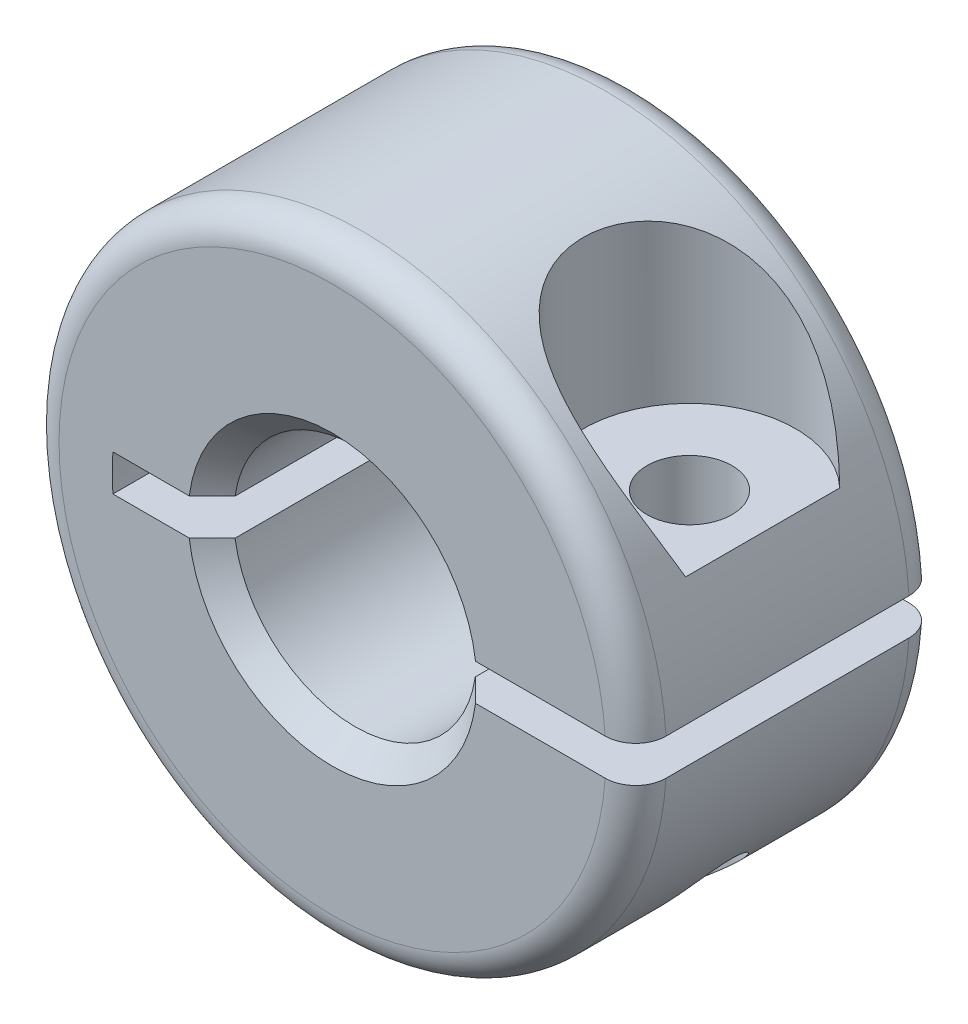
SolidWorks part; units mm, degrees
material "AISI 1020"
ref_plane "Přední rovina" through (0, 0, 0) normal (0, 0, 1) x (1, 0, 0)
ref_plane "Horní rovina" through (0, 0, 0) normal (0, 1, 0) x (1, 0, 0)
ref_plane "Pravá rovina" through (0, 0, 0) normal (1, 0, 0) x (0, 0, -1)
sketch "Skica1" plane through (0, 0, 0) normal (0, 0, 1) x (1, 0, 0)
  circle A0 centre (0, 0) radius 10
  circle A1 centre (0, 0) radius 4
  dimension "D1" = 8
  dimension "D2" = 20
extrude "Přidat vysunutím1" add sketch "Skica1" along normal blind 10
sketch "Skica2" plane through (0, 0, 10) normal (0, 0, 1) x (1, 0, 0)
  line L0 (-10, 0) -> (10, 0) construction
  line L2 (-7.2251, 0.6) -> (12.1108, 0.6)
  line L4 (-7.2251, -0.6) -> (12.1108, -0.6)
  line L5 (12.1108, 0.6) -> (12.1108, -0.6)
  line L6 (-8.6992, 0.6) -> (12.1108, -0.6) construction
  line L7 (-8.6992, -0.6) -> (12.1108, 0.6) construction
  arc A3 (-7.2251, 0.6) -> (-7.2251, -0.6) centre (0, 0) ccw
  point P9 (1.7058, 0)
  dimension "D1" = 1.2
extrude "Odebrat vysunutím1" cut sketch "Skica2" against normal blind 10
sketch "Skica3" plane through (0, -0.6, 0) normal (0, 1, 0) x (1, 0, 0)
  line L0 (9.982, -5) -> (-11.1644, -5) construction
  line L1 (9.982, 0) -> (9.982, -10) construction
  line L3 (6.7547, 0) -> (6.7547, -10) construction
  line L5 (3.9547, 0) -> (3.9547, -10) construction
  circle A0 centre (6.7547, -5) radius 1.375
  dimension "D1" = 2.75
  dimension "D2" = 2.8
extrude "Odebrat vysunutím2" cut sketch "Skica3" against normal blind 10
sketch "Skica4" plane through (0, 0.6, 0) normal (0, -1, 0) x (1, 0, 0)
  line L0 (9.982, 5) -> (3.9547, 5) construction
  line L1 (9.982, 10) -> (9.982, 0) construction
  line L2 (3.9547, 10) -> (3.9547, 0) construction
  line L3 (6.7547, 10) -> (6.7547, 0) construction
  circle A0 centre (6.7547, 5) radius 1.4
  dimension "D1" = 2.8
  dimension "D2" = 2.8
extrude "Odebrat vysunutím3" cut sketch "Skica4" against normal blind 10
ref_plane "Rovina1" through (0, 4, 0) normal (0, 1, 0) x (1, 0, 0)
sketch "Skica5" plane through (0, 4, 0) normal (0, 1, 0) x (1, 0, 0)
  circle A0 centre (6.7547, -5) radius 3.5
  dimension "D1" = 7
extrude "Odebrat vysunutím4" cut sketch "Skica5" along normal blind 10
fillet "Zaoblit1" radius 1 2 edges at (-10, 0, 0) (-10, 0, 10)
chamfer "Zkosení2" distance 0.75 angle 45 4 edges at (0, -4, 0) (0, 4, 0) (0, 4, 10) (0, -4, 10)
